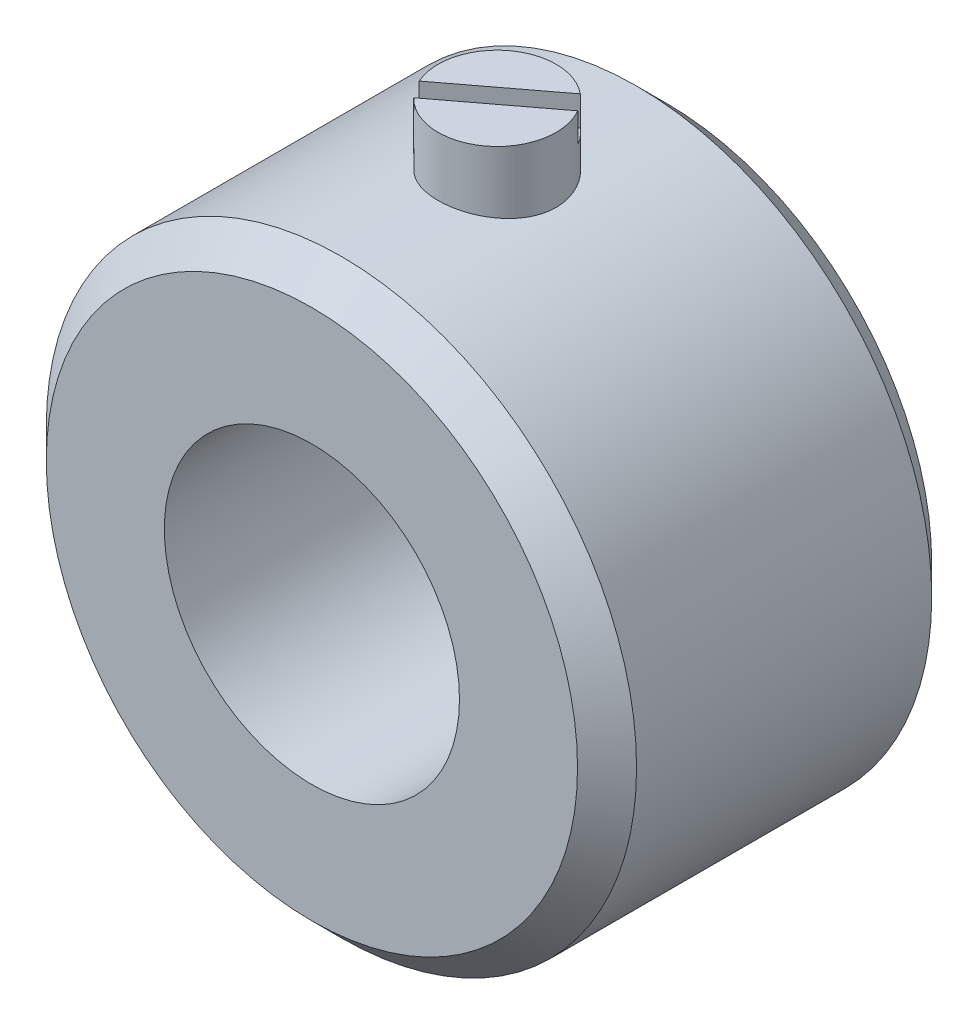
SolidWorks part; units mm, degrees
ref_plane "Front Plane" through (0, 0, 0) normal (0, 0, 1) x (1, 0, 0)
ref_plane "Top Plane" through (0, 0, 0) normal (0, 1, 0) x (1, 0, 0)
ref_plane "Right Plane" through (0, 0, 0) normal (1, 0, 0) x (0, 0, -1)
sketch "Sketch2" plane through (0, 0, 0) normal (0, 0, 1) x (1, 0, 0)
  circle A0 centre (0, 0) radius 2.5
  circle A1 centre (0, 0) radius 5
  dimension "D1" = 5
  dimension "D2" = 10
extrude "Boss-Extrude1" add sketch "Sketch2" along normal blind 6
chamfer "Chamfer1" distance 0.5 angle 45 1 edges at (5, 0, 6)
ref_plane "Plane1" through (0, 4, 0) normal (0, 1, 0) x (1, 0, 0)
sketch "Sketch4" plane through (0, 4, 0) normal (0, 1, 0) x (1, 0, 0)
  circle A0 centre (0, -2.8618) radius 1
  dimension "D1" = 2
extrude "Boss-Extrude2" add sketch "Sketch4" along normal blind 2
sketch "Sketch5" plane through (0, 6, 0) normal (0, 1, 0) x (1, 0, 0)
  line L0 (-1.1352, -3.4363) -> (0.892, -1.9005)
  line L1 (0.892, -1.9005) -> (1.105, -2.1817)
  line L2 (1.105, -2.1817) -> (-0.9222, -3.7175)
  line L3 (-0.9222, -3.7175) -> (-1.1352, -3.4363)
extrude "Cut-Extrude2" cut sketch "Sketch5" against normal blind 0.5
chamfer "Chamfer2" distance 0.5 angle 45 1 edges at (5, 0, 0)
